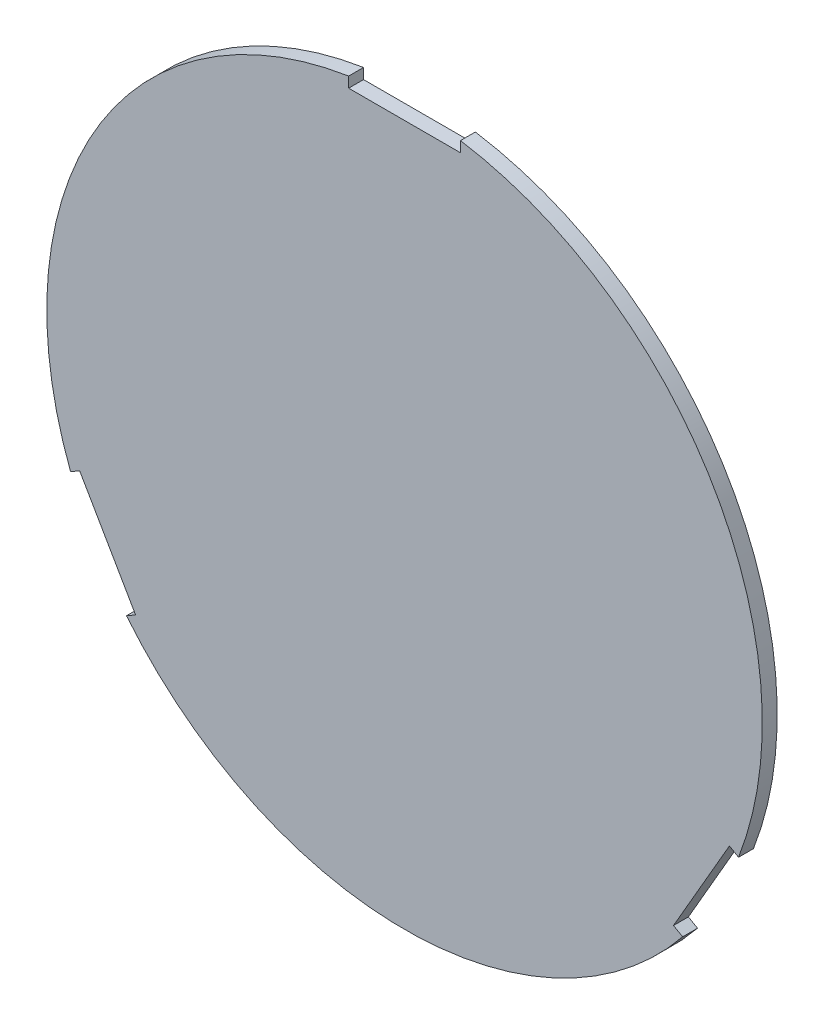
SolidWorks part; units mm, degrees
ref_plane "Спереди" through (0, 0, 0) normal (0, 0, 1) x (1, 0, 0)
ref_plane "Сверху" through (0, 0, 0) normal (0, 1, 0) x (1, 0, 0)
ref_plane "Справа" through (0, 0, 0) normal (1, 0, 0) x (0, 0, -1)
sketch "Эскиз1" plane through (0, 0, 0) normal (0, 0, 1) x (1, 0, 0)
  line L0 (0, 70.3316) -> (0, -107.3861) construction
  line L1 (47.0513, -18.5048) -> (39.5513, -31.4952)
  line L2 (-7.5, 50) -> (7.5, 50)
  line L3 (-7.5, 50) -> (-7.5, 46)
  line L4 (-7.5, 46) -> (7.5, 46)
  line L5 (7.5, 50) -> (7.5, 46)
  line L6 (-7.5, 50) -> (7.5, 46) construction
  line L7 (-7.5, 46) -> (7.5, 50) construction
  line L8 (47.0513, -18.5048) -> (43.5872, -16.5048)
  line L9 (43.5872, -16.5048) -> (36.0872, -29.4952)
  line L10 (39.5513, -31.4952) -> (36.0872, -29.4952)
  line L11 (47.0513, -18.5048) -> (36.0872, -29.4952) construction
  line L12 (43.5872, -16.5048) -> (39.5513, -31.4952) construction
  line L13 (-39.5513, -31.4952) -> (-47.0513, -18.5048)
  line L14 (-39.5513, -31.4952) -> (-36.0872, -29.4952)
  line L15 (-36.0872, -29.4952) -> (-43.5872, -16.5048)
  line L16 (-47.0513, -18.5048) -> (-43.5872, -16.5048)
  line L17 (-39.5513, -31.4952) -> (-43.5872, -16.5048) construction
  line L18 (-36.0872, -29.4952) -> (-47.0513, -18.5048) construction
  circle A0 centre (0, 0) radius 48
  point P9 (0, 48)
  point P17 (41.5692, -24)
  point P22 (-41.5692, -24)
  point P23 (0, 0)
  dimension "D1" = 96
  dimension "D2" = 2
  dimension "D3" = 15
  dimension "D4" = 3
extrude "Бобышка-Вытянуть1" add sketch "Эскиз1" along normal blind 2 contours L5 A0 L3 L4 | L16 A0 L14 L15 | L10 A0 L8 L9
